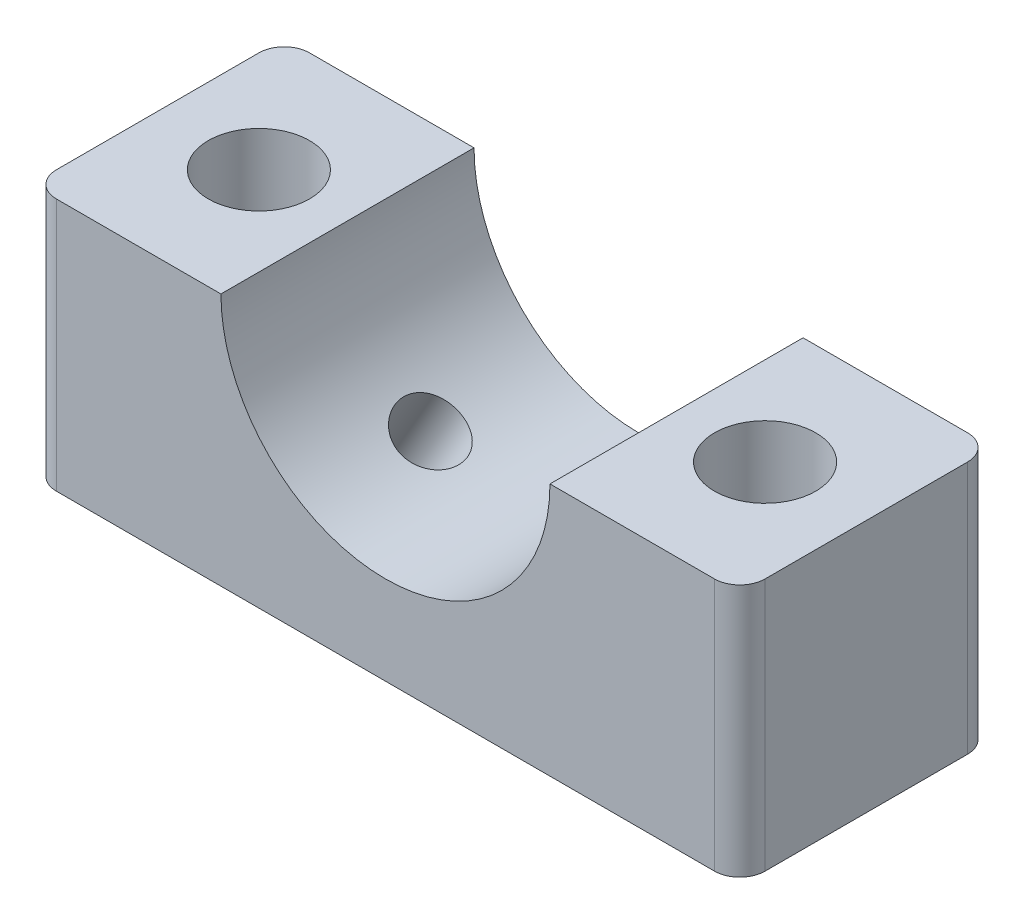
SolidWorks part; units mm, degrees
ref_plane "Front Plane" through (0, 0, 0) normal (0, 0, 1) x (1, 0, 0)
ref_plane "Top Plane" through (0, 0, 0) normal (0, 1, 0) x (1, 0, 0)
ref_plane "Right Plane" through (0, 0, 0) normal (1, 0, 0) x (0, 0, -1)
sketch "Sketch1" plane through (0, 0, 0) normal (0, 0, 1) x (1, 0, 0)
  line L0 (-14, 0) -> (14, 0)
  line L1 (-14, 10) -> (-6.5, 10)
  line L2 (-14, 10) -> (-14, 0)
  line L4 (14, 10) -> (14, 0)
  line L5 (6.5, 10) -> (14, 10)
  arc A0 (-6.5, 10) -> (6.5, 10) centre (0, 10) ccw
  point P0 (0, 0)
  point P9 (0, 0)
  dimension "D3" = 6.5
  dimension "D1" = 10
  dimension "D2" = 28
extrude "Boss-Extrude1" add sketch "Sketch1" along normal mid plane 10
sketch "Sketch2" plane through (0, 0, 0) normal (0, 0, 1) x (1, 0, 0)
  line L1 (-2.7484, 5.2396) -> (-7.6059, -3.1738)
  line L2 (-7.6059, -3.1738) -> (-8.6884, -2.5488)
  line L3 (-8.6884, -2.5488) -> (-3.831, 5.8646)
  line L4 (-3.831, 5.8646) -> (-2.7484, 5.2396)
  dimension "D2" = 1.25
  dimension "D3" = 1.25
revolve "Cut-Revolve2" cut sketch "Sketch2" angle 360 about L1
sketch "Sketch4" plane through (0, 10, 0) normal (0, 1, 0) x (1, 0, 0)
  line L0 (-14, -5) -> (-14, 5) construction
  circle A0 centre (-10, 0) radius 2
  circle A1 centre (10, 0) radius 2
  dimension "D1" = 10
  dimension "D2" = 10
  dimension "D3" = 4
  dimension "D4" = 4
extrude "Cut-Extrude1" cut sketch "Sketch4" against normal up to next
fillet "Fillet1" radius 1 4 edges at (-14, 5, -5) (14, 5, -5) (14, 5, 5) (-14, 5, 5)
